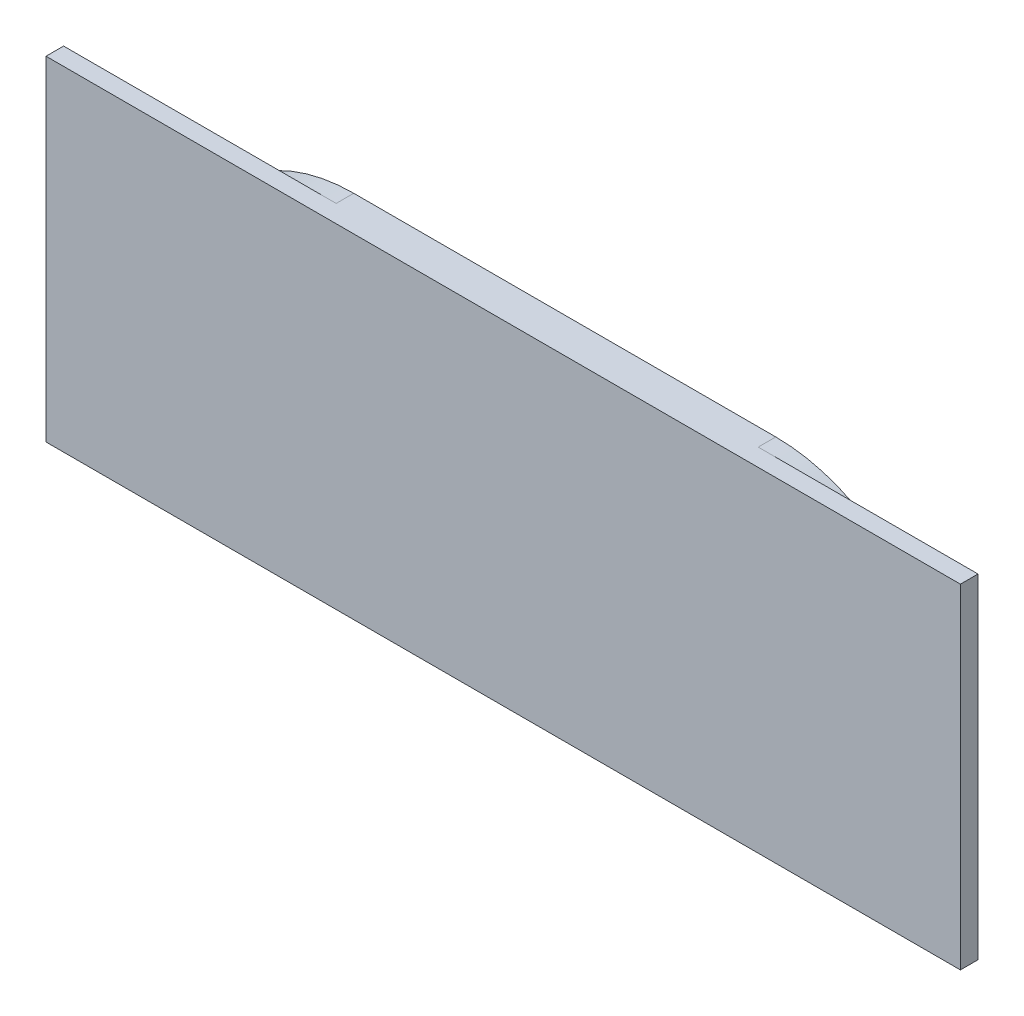
SolidWorks part; units mm, degrees
ref_plane "Alzado" through (0, 0, 0) normal (0, 0, 1) x (1, 0, 0)
ref_plane "Planta" through (0, 0, 0) normal (0, 1, 0) x (1, 0, 0)
ref_plane "Vista lateral" through (0, 0, 0) normal (1, 0, 0) x (0, 0, -1)
sketch "Croquis1" plane through (0, 0, 0) normal (0, 0, 1) x (1, 0, 0)
  line L0 (-102.799, 22.9096) -> (-78.799, 22.9096)
  line L2 (-102.799, 3.9096) -> (-78.799, 3.9096)
  arc A0 (-78.799, 22.9096) -> (-78.799, 3.9096) centre (-78.799, 13.4096) cw
  arc A1 (-102.799, 22.9096) -> (-102.799, 3.9096) centre (-102.799, 13.4096) ccw
extrude "Saliente-Extruir1" add sketch "Croquis1" along normal blind 1
sketch "Croquis2" plane through (0, 0, 1) normal (0, 0, 1) x (1, 0, 0)
  line L0 (-90.799, 22.9096) -> (-118.299, 22.9096)
  line L1 (-78.799, 22.9096) -> (-102.799, 22.9096) construction
  line L2 (-118.299, 22.9096) -> (-118.299, 3.9096)
  line L3 (-118.299, 3.9096) -> (-66.299, 3.9096)
  line L4 (-66.299, 3.9096) -> (-66.299, 22.9096)
  line L5 (-66.299, 22.9096) -> (-90.799, 22.9096)
extrude "Saliente-Extruir2" add sketch "Croquis2" along normal blind 1
